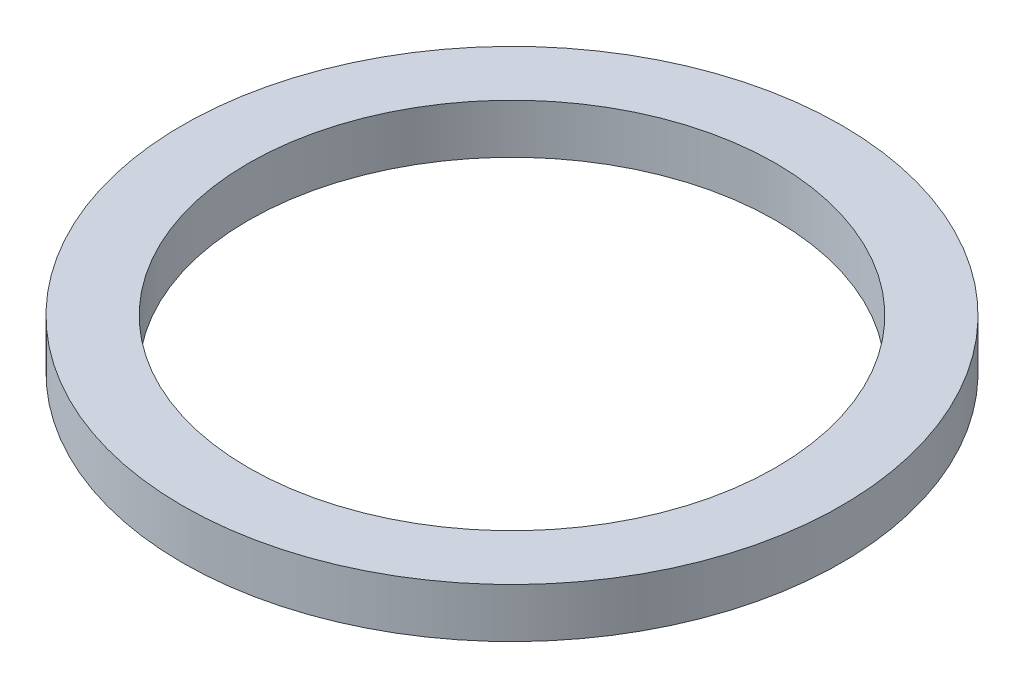
SolidWorks part; units mm, degrees
material "Silicon Rubber"
ref_plane "Front" through (0, 0, 0) normal (0, 0, 1) x (1, 0, 0)
ref_plane "Top" through (0, 0, 0) normal (0, 1, 0) x (1, 0, 0)
ref_plane "Right" through (0, 0, 0) normal (1, 0, 0) x (0, 0, -1)
sketch "Sketch1" plane through (0, 0, 0) normal (0, 0, 1) x (1, 0, 0)
  line L0 (-8, 0) -> (0, 0) construction
  line L1 (-10, 0.75) -> (-8, 0.75)
  line L2 (-10, 0.75) -> (-10, -0.75)
  line L3 (-10, -0.75) -> (-8, -0.75)
  line L4 (-8, 0.75) -> (-8, -0.75)
  line L5 (0, 0) -> (0, 3.8277) construction
  dimension "D1" = 20
  dimension "D2" = 16
  dimension "D3" = 1.5
revolve "Revolve1" add sketch "Sketch1" angle 360 about L5
